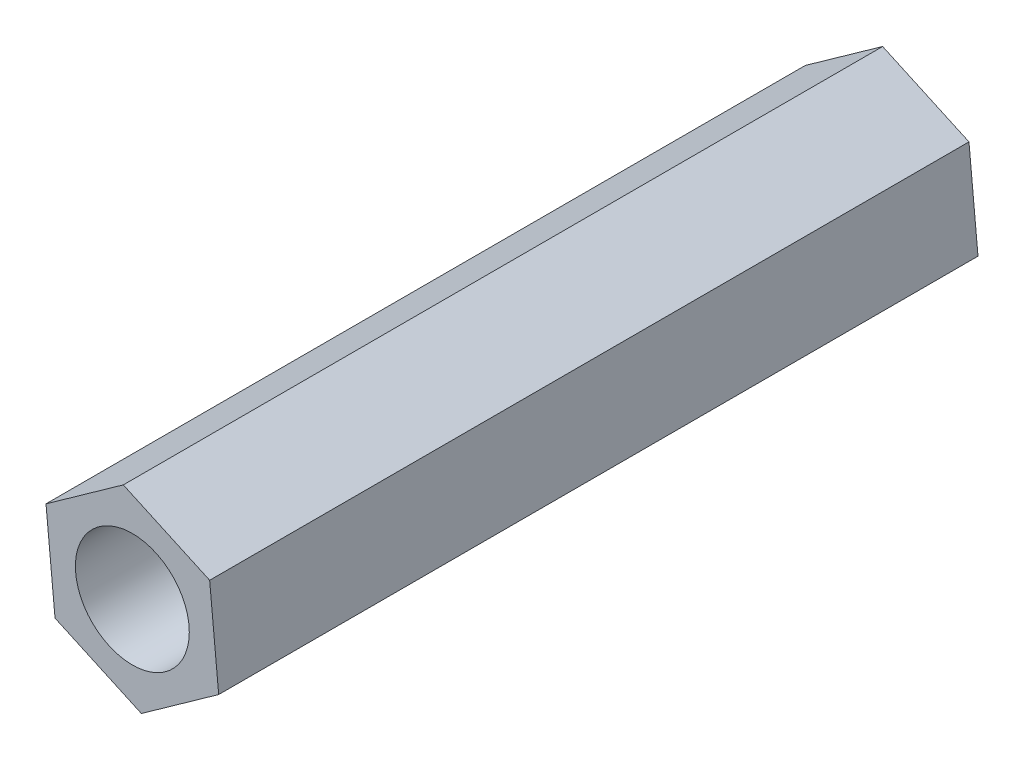
SolidWorks part; units mm, degrees
ref_plane "Front Plane" through (0, 0, 0) normal (0, 0, 1) x (1, 0, 0)
ref_plane "Top Plane" through (0, 0, 0) normal (0, 1, 0) x (1, 0, 0)
ref_plane "Right Plane" through (0, 0, 0) normal (1, 0, 0) x (0, 0, -1)
sketch "Sketch1" plane through (0, 0, 0) normal (0, 0, 1) x (1, 0, 0)
  line L1 (2.0364, 1.4502) -> (-0.2377, 2.4887)
  line L2 (-0.2377, 2.4887) -> (-2.2741, 1.0385)
  line L3 (-2.2741, 1.0385) -> (-2.0364, -1.4502)
  line L4 (-2.0364, -1.4502) -> (0.2377, -2.4887)
  line L5 (0.2377, -2.4887) -> (2.2741, -1.0385)
  line L6 (2.2741, -1.0385) -> (2.0364, 1.4502)
  circle A0 centre (0, 0) radius 1.5
  circle A1 centre (0, 0) radius 2.1651 construction
  dimension "D1" = 3
  dimension "D2" = 2.5
extrude "Boss-Extrude1" add sketch "Sketch1" along normal blind 20
